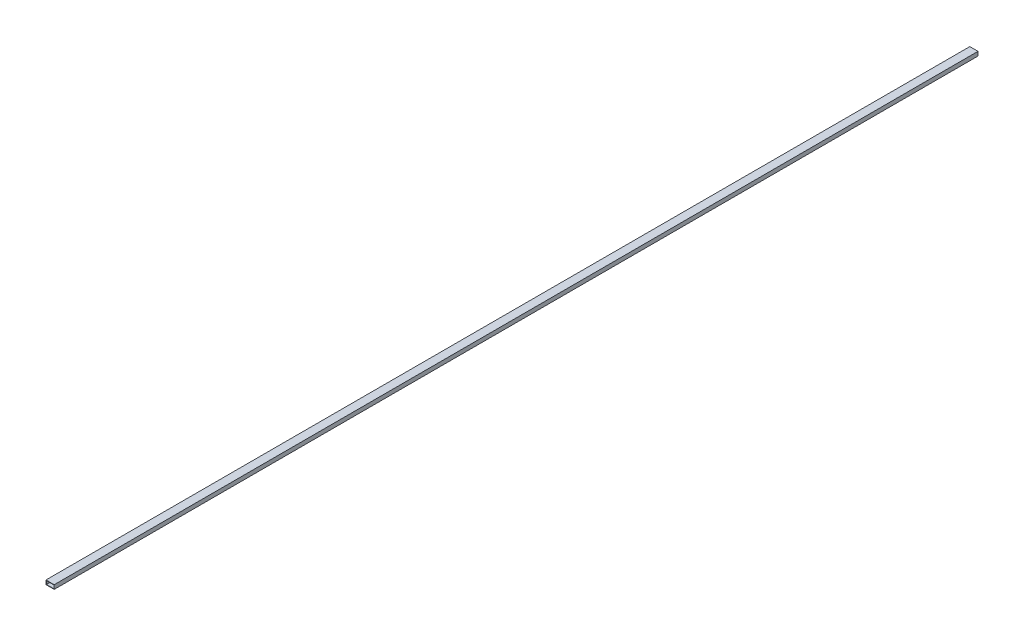
SolidWorks part; units mm, degrees
material "1100-H18 棒材(SS)"
ref_plane "前视基准面" through (0, 0, 0) normal (0, 0, 1) x (1, 0, 0)
ref_plane "上视基准面" through (0, 0, 0) normal (0, 1, 0) x (1, 0, 0)
ref_plane "右视基准面" through (0, 0, 0) normal (1, 0, 0) x (0, 0, -1)
other "Configuration Table"
sketch "草图1" plane through (0, 0, 0) normal (0, 0, 1) x (1, 0, 0)
  line L1 (0, 0) -> (20, 0)
  line L2 (0, 0) -> (0, 10)
  line L3 (0, 10) -> (20, 10)
  line L4 (20, 0) -> (20, 10)
  line L5 (1, 1) -> (19, 1)
  line L6 (1, 1) -> (1, 9)
  line L7 (1, 9) -> (19, 9)
  line L8 (19, 1) -> (19, 9)
  dimension "D1" = 20
  dimension "D2" = 10
  dimension "D3" = 1
  dimension "D4" = 1
  dimension "D5" = 1
  dimension "D6" = 1
extrude "凸台-拉伸1" add sketch "草图1" along normal blind 2250
